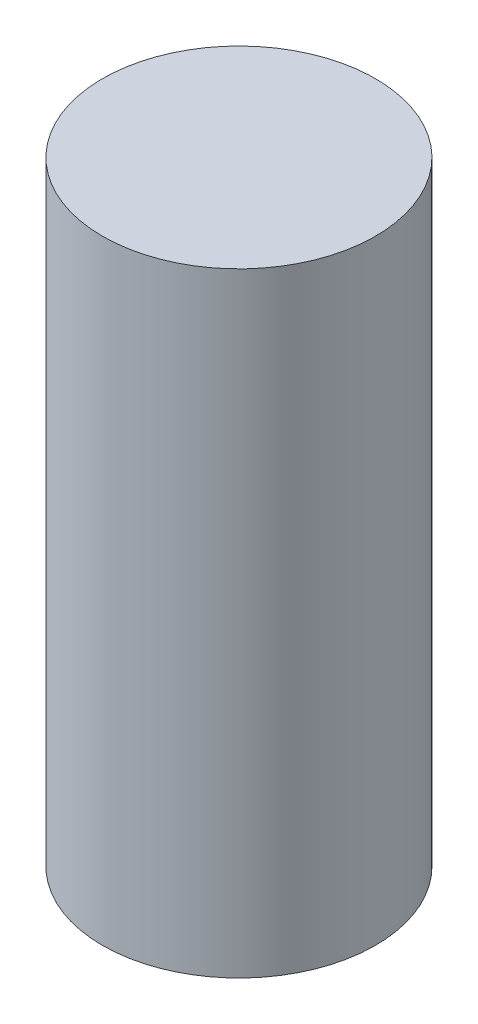
SolidWorks part; units mm, degrees
ref_plane "Front Plane" through (0, 0, 0) normal (0, 0, 1) x (1, 0, 0)
ref_plane "Top Plane" through (0, 0, 0) normal (0, 1, 0) x (1, 0, 0)
ref_plane "Right Plane" through (0, 0, 0) normal (1, 0, 0) x (0, 0, -1)
sketch "Sketch1" plane through (0, 0, 0) normal (0, 1, 0) x (1, 0, 0)
  circle A0 centre (0, 0) radius 4
  dimension "D1" = 8
extrude "Boss-Extrude1" add sketch "Sketch1" along normal blind 18
